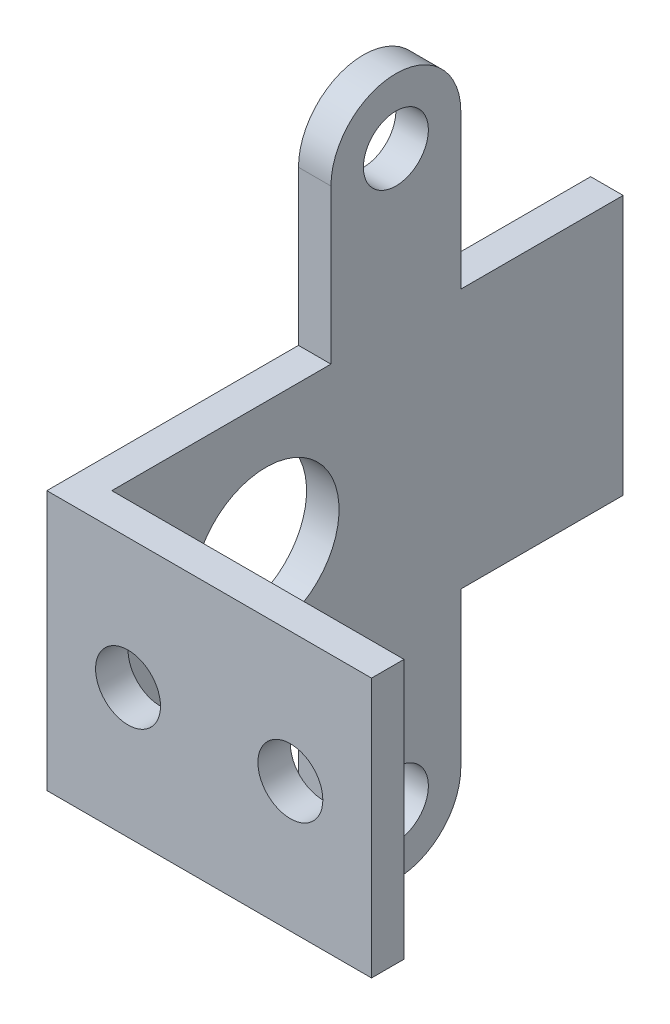
SolidWorks part; units mm, degrees
ref_plane "Front Plane" through (0, 0, 0) normal (0, 0, 1) x (1, 0, 0)
ref_plane "Top Plane" through (0, 0, 0) normal (0, 1, 0) x (1, 0, 0)
ref_plane "Right Plane" through (0, 0, 0) normal (1, 0, 0) x (0, 0, -1)
sketch "Sketch1" plane through (0, 0, 0) normal (0, 1, 0) x (1, 0, 0)
  line L0 (-4.6207, 26) -> (-4.6207, -7.5)
  line L1 (-4.6207, 26) -> (-2.6207, 26)
  line L4 (-2.6207, 26) -> (-2.6207, -5.5)
  line L5 (-2.6207, -5.5) -> (15.3793, -5.5)
  line L7 (-4.6207, -7.5) -> (15.3793, -7.5)
  line L8 (15.3793, -5.5) -> (15.3793, -7.5)
  dimension "D1" = 2
  dimension "D2" = 2
  dimension "D3" = 33.5
  dimension "D4" = 20
extrude "Boss-Extrude1" add sketch "Sketch1" along normal blind 16
sketch "Sketch2" plane through (0, 0, 7.5) normal (0, 0, 1) x (1, 0, 0)
  line L0 (-4.6207, 0) -> (15.3793, 0) construction
  line L1 (15.3793, 16) -> (15.3793, 0) construction
  circle A0 centre (0.3793, 8) radius 2
  circle A1 centre (10.3793, 8) radius 2
  dimension "D1" = 4
  dimension "D2" = 4
  dimension "D3" = 8
  dimension "D4" = 8
  dimension "D5" = 5
  dimension "D6" = 10
extrude "Cut-Extrude1" cut sketch "Sketch2" against normal blind 16
sketch "Sketch3" plane through (-4.6207, 0, 0) normal (-1, 0, 0) x (0, 0, 1)
  line L0 (-26, 16) -> (7.5, 16) construction
  line L1 (-16, 16) -> (-8, 16)
  line L2 (-16, 16) -> (-16, 25.5)
  line L4 (-8, 16) -> (-8, 25.5)
  line L5 (-26, 0) -> (7.5, 0) construction
  line L6 (-16, 0) -> (-8, 0)
  line L7 (-16, 0) -> (-16, -9.5)
  line L9 (-8, 0) -> (-8, -9.5)
  line L10 (-12, 25.5) -> (-12, -9.5) construction
  line L11 (-26, 16) -> (-26, 0) construction
  arc A1 (-16, -9.5) -> (-8, -9.5) centre (-12, -9.5) ccw
  arc A2 (-8, 25.5) -> (-16, 25.5) centre (-12, 25.5) ccw
  circle A3 centre (-12, -9.5) radius 2
  circle A4 centre (-12, 25.5) radius 2
  point P18 (-26, 8)
  dimension "D3" = 4
  dimension "D4" = 4
  dimension "D1" = 8
  dimension "D2" = 8
  dimension "D5" = 9.5
  dimension "D6" = 9.5
  dimension "D7" = 14
extrude "Boss-Extrude2" add sketch "Sketch3" against normal blind 2
sketch "Sketch4" plane through (-4.6207, 0, 0) normal (-1, 0, 0) x (0, 0, 1)
  line L0 (-8, 0) -> (7.5, 0) construction
  line L1 (-26, 16) -> (-26, 0) construction
  circle A0 centre (-4, 8) radius 4.5
  dimension "D3" = 9
  dimension "D1" = 8
  dimension "D2" = 22
extrude "Cut-Extrude2" cut sketch "Sketch4" against normal blind 2
